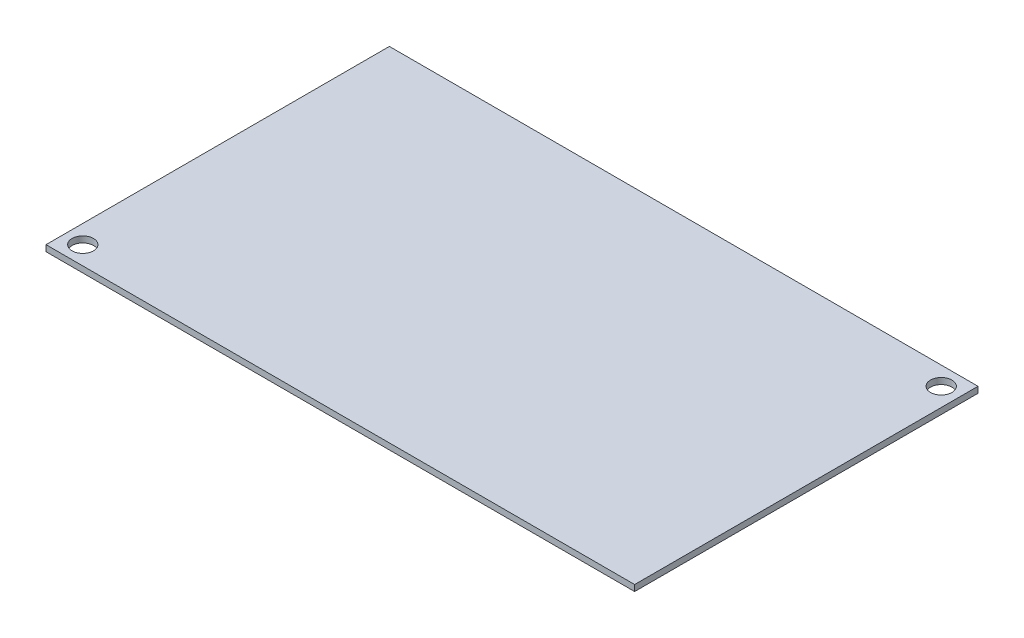
SolidWorks part; units mm, degrees
ref_plane "Front Plane" through (0, 0, 0) normal (0, 0, 1) x (1, 0, 0)
ref_plane "Top Plane" through (0, 0, 0) normal (0, 1, 0) x (1, 0, 0)
ref_plane "Right Plane" through (0, 0, 0) normal (1, 0, 0) x (0, 0, -1)
sketch "Sketch1" plane through (0, 0, 0) normal (0, 1, 0) x (1, 0, 0)
  line L1 (0, 0) -> (121.92, 0)
  line L2 (0, 0) -> (0, 71.12)
  line L3 (0, 71.12) -> (121.92, 71.12)
  line L4 (121.92, 0) -> (121.92, 71.12)
  circle A0 centre (3.81, 3.81) radius 2.2225
  circle A1 centre (118.11, 67.31) radius 2.2225
  dimension "D3" = 4.445
  dimension "D4" = 4.445
  dimension "D5" = 63.5
  dimension "D6" = 114.3
  dimension "D7" = 3.81
  dimension "D8" = 3.81
  dimension "D1" = 71.12
  dimension "D2" = 121.92
extrude "Extrude1" add sketch "Sketch1" along normal blind 1.27
